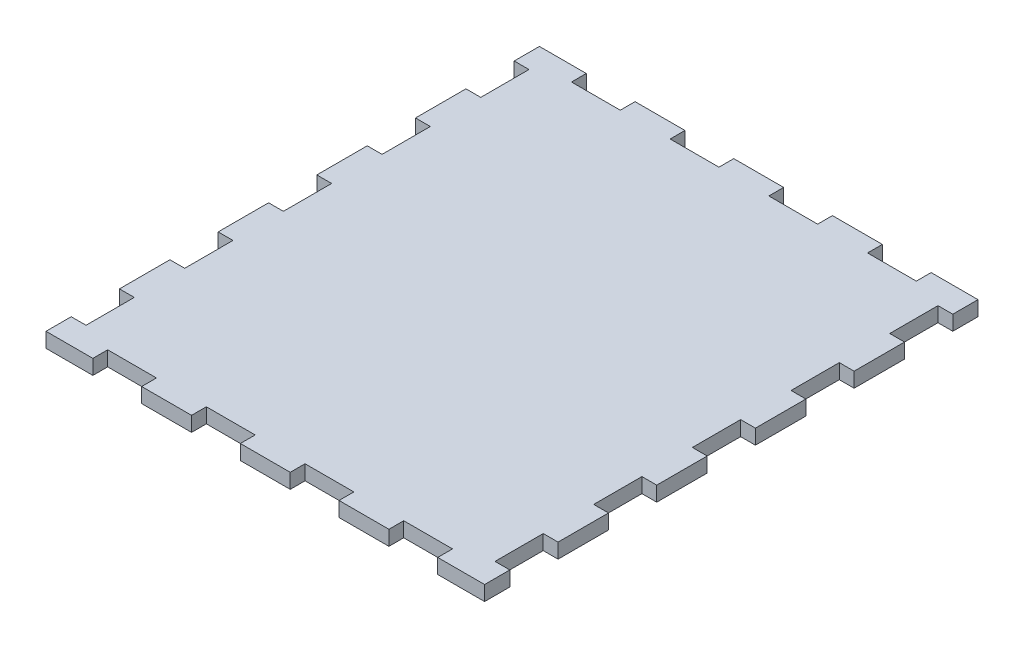
SolidWorks part; units mm, degrees
ref_plane "Plan de face" through (0, 0, 0) normal (0, 0, 1) x (1, 0, 0)
ref_plane "Plan de dessus" through (0, 0, 0) normal (0, 1, 0) x (1, 0, 0)
ref_plane "Plan de droite" through (0, 0, 0) normal (1, 0, 0) x (0, 0, -1)
sketch "Esquisse1" plane through (0, 0, 0) normal (0, 1, 0) x (1, 0, 0)
  line L0 (0, 0) -> (167.2792, 0) construction
  line L1 (0, 0) -> (127.2792, 45) construction
  line L2 (127.2792, 45) -> (207.2792, 45)
  line L3 (127.2792, 45) -> (127.2792, -45)
  line L4 (127.2792, -45) -> (207.2792, -45)
  line L5 (207.2792, 45) -> (207.2792, -45)
  line L6 (127.2792, 45) -> (207.2792, -45) construction
  line L7 (127.2792, -45) -> (207.2792, 45) construction
  line L8 (0, 0) -> (150.2289, 62.2269) construction
  dimension "D1" = 135
  dimension "D2" = 22.5
  dimension "D3" = 80
  dimension "D4" = 90
extrude "Boss.-Extru.1" add sketch "Esquisse1" along normal blind 2.7
ref_plane "Plan1" through (167.2792, 0, 0) normal (1, 0, 0) x (0, 0, -1)
sketch "Esquisse2" plane through (0, 0, 0) normal (0, 1, 0) x (1, 0, 0)
  line L0 (207.2792, -45) -> (207.2792, 45) construction
  line L1 (207.2792, 4.4) -> (204.5792, 4.4)
  line L2 (207.2792, 4.4) -> (207.2792, -4.4)
  line L3 (207.2792, -4.4) -> (204.5792, -4.4)
  line L4 (204.5792, 4.4) -> (204.5792, -4.4)
  line L5 (127.2792, 0) -> (204.5792, 0) construction
  line L6 (127.2792, 45) -> (127.2792, -45) construction
  dimension "D1" = 8.8
  dimension "D2" = 2.7
extrude "Enlèv. mat.-Extru.1" cut sketch "Esquisse2" along normal blind 2.7
pattern_linear "Répétition linéaire1" count 3 spacing 18 along (0, 0, 1) count 3 spacing 18 along (0, 0, -1) of "Enlèv. mat.-Extru.1"
mirror "Symétrie1" about plane through (167.2792, 0, 0) normal (1, 0, 0) of "Répétition linéaire1", "Enlèv. mat.-Extru.1"
sketch "Esquisse3" plane through (0, 0, 0) normal (0, 1, 0) x (1, 0, 0)
  line L0 (207.2792, 45) -> (127.2792, 45) construction
  line L1 (171.8292, 45) -> (180.7292, 45)
  line L2 (171.8292, 45) -> (171.8292, 42.3)
  line L3 (171.8292, 42.3) -> (180.7292, 42.3)
  line L4 (180.7292, 45) -> (180.7292, 42.3)
  line L5 (176.2792, 45) -> (176.2792, 42.3) construction
  line L6 (167.2792, -1.485) -> (167.2792, 1.485) construction
  dimension "D1" = 9
  dimension "D2" = 8.9
  dimension "D3" = 2.7
extrude "Enlèv. mat.-Extru.2" cut sketch "Esquisse3" along normal blind 2.7
pattern_linear "Répétition linéaire2" count 2 spacing 18 along (1, 0, 0) count 3 spacing 18 along (-1, 0, 0) of "Enlèv. mat.-Extru.2"
mirror "Symétrie2" about plane through (0, 0, 0) normal (0, 0, 1) of "Répétition linéaire2", "Enlèv. mat.-Extru.2"
